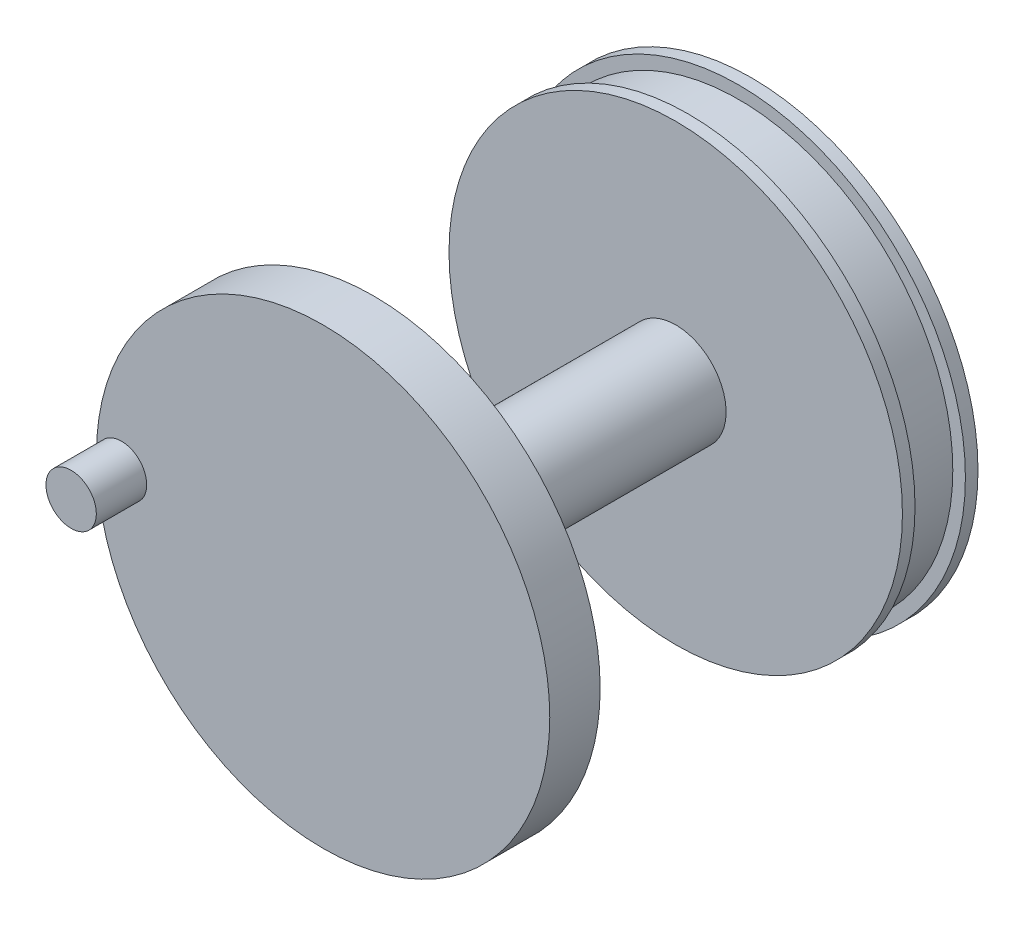
SolidWorks part; units mm, degrees
ref_plane "Front Plane" through (0, 0, 0) normal (0, 0, 1) x (1, 0, 0)
ref_plane "Top Plane" through (0, 0, 0) normal (0, 1, 0) x (1, 0, 0)
ref_plane "Right Plane" through (0, 0, 0) normal (1, 0, 0) x (0, 0, -1)
sketch "Sketch1" plane through (0, 0, 0) normal (0, 0, 1) x (1, 0, 0)
  circle A0 centre (0, 0) radius 45
  dimension "D1" = 90
extrude "Boss-Extrude1" add sketch "Sketch1" along normal blind 10
ref_plane "Plane1" through (0, 0, 20) normal (0, 0, 1) x (1, 0, 0)
sketch "Sketch2" plane through (0, 0, 20) normal (0, 0, 1) x (1, 0, 0)
  line L0 (-45, 0) -> (45, 0) construction
  line L1 (0, 45) -> (0, -45) construction
  line L2 (-40, 5) -> (-40, -5) construction
  circle A0 centre (0, 0) radius 45 construction
  circle A1 centre (-40, 0) radius 5
  dimension "D1" = 10
extrude "Boss-Extrude2" add sketch "Sketch2" against normal blind 10
sketch "Sketch3" plane through (0, 0, 0) normal (0, 0, -1) x (-1, 0, 0)
  circle A0 centre (0, 0) radius 10
  dimension "D1" = 20
extrude "Boss-Extrude3" add sketch "Sketch3" along normal blind 60
sketch "Sketch4" plane through (0, 0, -60) normal (0, 0, -1) x (-1, 0, 0)
  circle A0 centre (0, 0) radius 45
extrude "Boss-Extrude4" add sketch "Sketch4" along normal blind 15
sketch "Sketch5" plane through (0, 0, -75) normal (0, 0, -1) x (-1, 0, 0)
  circle A0 centre (0, 0) radius 45
  circle A1 centre (0, 0) radius 42.5
  dimension "D1" = 90
  dimension "D2" = 2.5
extrude "Cut-Extrude1" cut sketch "Sketch5" against normal blind 10 from offset 2.5 offset against normal yes
